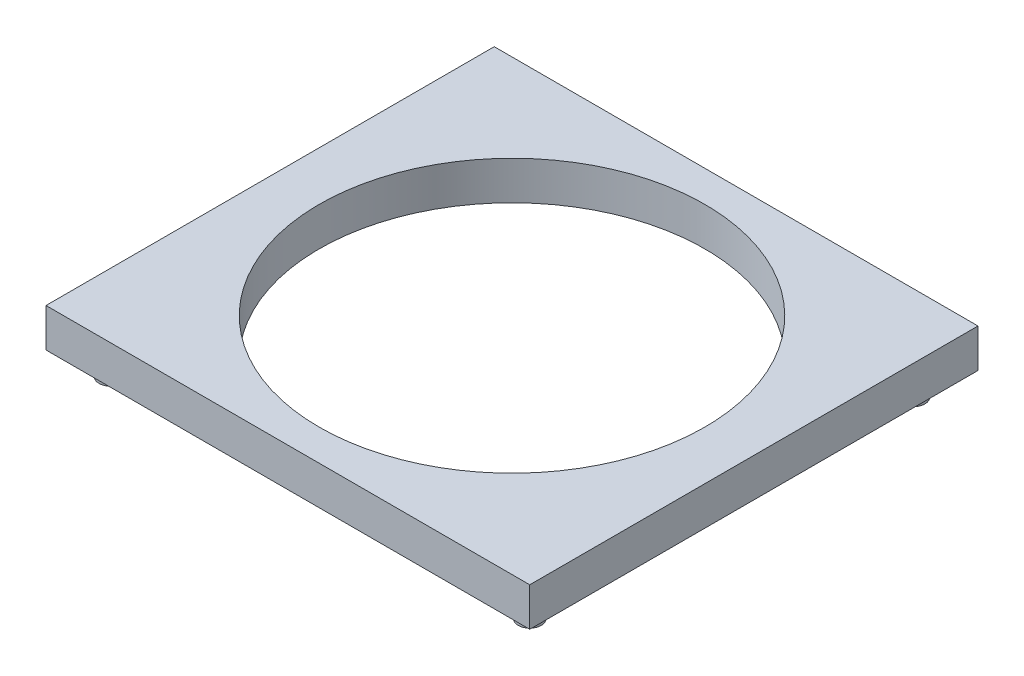
SolidWorks part; units mm, degrees
ref_plane "Front Plane" through (0, 0, 0) normal (0, 0, 1) x (1, 0, 0)
ref_plane "Top Plane" through (0, 0, 0) normal (0, 1, 0) x (1, 0, 0)
ref_plane "Right Plane" through (0, 0, 0) normal (1, 0, 0) x (0, 0, -1)
sketch "Sketch1" plane through (0, 0, 0) normal (0, 1, 0) x (1, 0, 0)
  line L1 (-31.35, -29.05) -> (31.35, -29.05)
  line L2 (-31.35, -29.05) -> (-31.35, 29.05)
  line L3 (-31.35, 29.05) -> (31.35, 29.05)
  line L4 (31.35, -29.05) -> (31.35, 29.05)
  line L5 (-31.35, -29.05) -> (31.35, 29.05) construction
  line L6 (-31.35, 29.05) -> (31.35, -29.05) construction
  circle A0 centre (0, 0) radius 25
  dimension "D3" = 50
  dimension "D1" = 62.7
  dimension "D2" = 58.1
extrude "Boss-Extrude1" add sketch "Sketch1" along normal blind 5
sketch "Sketch2" plane through (0, 0, 0) normal (0, -1, 0) x (1, 0, 0)
  line L0 (0, 0) -> (0, 29.05) construction
  line L1 (-31.35, 29.05) -> (31.35, 29.05) construction
  line L2 (0, 0) -> (31.35, 0) construction
  line L3 (31.35, 29.05) -> (31.35, -29.05) construction
  line L4 (-27.1634, 24.8634) -> (-27.1634, 29.05) construction
  line L5 (-27.1634, 24.8634) -> (-31.35, 24.8634) construction
  line L6 (-31.35, -29.05) -> (-31.35, 29.05) construction
  line L7 (-27.1634, 24.8634) -> (-31.35, 29.05) construction
  line L8 (-27.1634, 24.8634) -> (-22.9768, 20.6768) construction
  line L9 (-22.9768, 20.6768) -> (-18.7902, 16.4902) construction
  circle A0 centre (-27.1634, 24.8634) radius 1.5
  circle A1 centre (27.1634, 24.8634) radius 1.5
  circle A2 centre (27.1634, -24.8634) radius 1.5
  circle A3 centre (-27.1634, -24.8634) radius 1.5
  circle A4 centre (0, 0) radius 25 construction
  dimension "D1" = 3
extrude "Boss-Extrude2" add sketch "Sketch2" along normal blind 3
